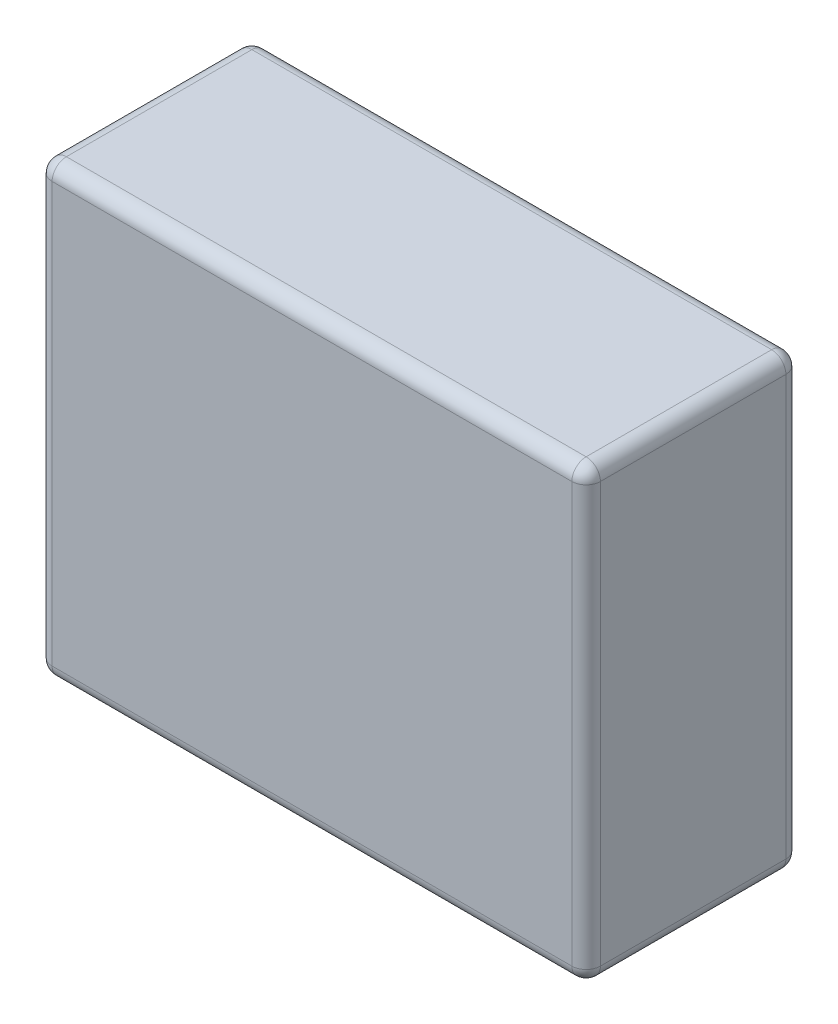
SolidWorks part; units mm, degrees
ref_plane "Alzado" through (0, 0, 0) normal (0, 0, 1) x (1, 0, 0)
ref_plane "Planta" through (0, 0, 0) normal (0, 1, 0) x (1, 0, 0)
ref_plane "Vista lateral" through (0, 0, 0) normal (1, 0, 0) x (0, 0, -1)
sketch "Croquis3" plane through (0, 0, 0) normal (0, 0, 1) x (1, 0, 0)
  line L1 (0, 62.8287) -> (76.8518, 62.8287)
  line L2 (0, 62.8287) -> (0, 0)
  line L3 (0, 0) -> (76.8518, 0)
  line L4 (76.8518, 62.8287) -> (76.8518, 0)
  point P4 (57.7107, 0.3153)
  point P5 (57.7634, 1.7407)
  point P6 (0, 0)
  point P8 (0, 0)
  point P9 (0, 0)
  point P10 (0, 0)
  point P11 (70.0748, 55.0227)
  point P12 (0, 0)
  point P13 (0, 0)
extrude "Saliente-Extruir1" add sketch "Croquis3" along normal blind 30 contours L2 L1 L4 L3
sketch "Croquis4" plane through (0, 0, 0) normal (0, 0, 1) x (1, 0, 0)
  line L1 (4, 4) -> (73, 4)
  line L2 (4, 4) -> (4, 59)
  line L3 (4, 59) -> (73, 59)
  line L4 (73, 4) -> (73, 59)
  point P4 (0, 0)
  point P5 (0, 0)
  point P6 (0, 0)
extrude "Cortar-Extruir1" cut sketch "Croquis4" along normal blind 26 contours L2 L1 L4 L3
fillet "Redondeo5" radius 2 4 edges at (0, 62.8287, 15) (0, 0, 15) (76.8518, 0, 15) (76.8518, 62.8287, 15)
fillet "Redondeo6" radius 2 8 edges at (76.266, 62.2429, 0) (0.5858, 62.2429, 0) (0.5858, 0.5858, 0) (76.266, 0.5858, 0) (38.4259, 0, 0) (0, 31.4144, 0) (38.4259, 62.8287, 0) (76.8518, 31.4144, 0)
fillet "Redondeo7" radius 2 8 edges at (76.266, 62.2429, 30) (0.5858, 62.2429, 30) (0.5858, 0.5858, 30) (76.266, 0.5858, 30) (0, 31.4144, 30) (38.4259, 62.8287, 30) (38.4259, 0, 30) (76.8518, 31.4144, 30)
sketch "Croquis5" plane through (0, 0, 0) normal (1, 0, 0) x (0, 0, -1)
  line L1 (-3, 59) -> (0, 59)
  line L2 (-3, 59) -> (-3, 4)
  line L3 (-3, 4) -> (0, 4)
  line L4 (0, 59) -> (0, 4)
  point P4 (0, 0)
  point P5 (0, 0)
  point P6 (0, 0)
  point P7 (0, 0)
  point P8 (0, 0)
extrude "Cortar-Extruir2" cut sketch "Croquis5" along normal blind 70
sketch "Croquis6" plane through (0, 0, 0) normal (1, 0, 0) x (0, 0, -1)
  line L1 (-3, 60.4) -> (-1.4, 60.4)
  line L2 (-3, 60.4) -> (-3, 2.6)
  line L3 (-3, 2.6) -> (-1.4, 2.6)
  line L4 (-1.4, 60.4) -> (-1.4, 2.6)
  point P4 (0, 0)
  point P5 (0, 0)
  point P6 (0, 0)
  point P7 (0, 0)
  point P8 (0, 0)
extrude "Cortar-Extruir3" cut sketch "Croquis6" along normal blind 73 contours L2 L1 L4 L3
